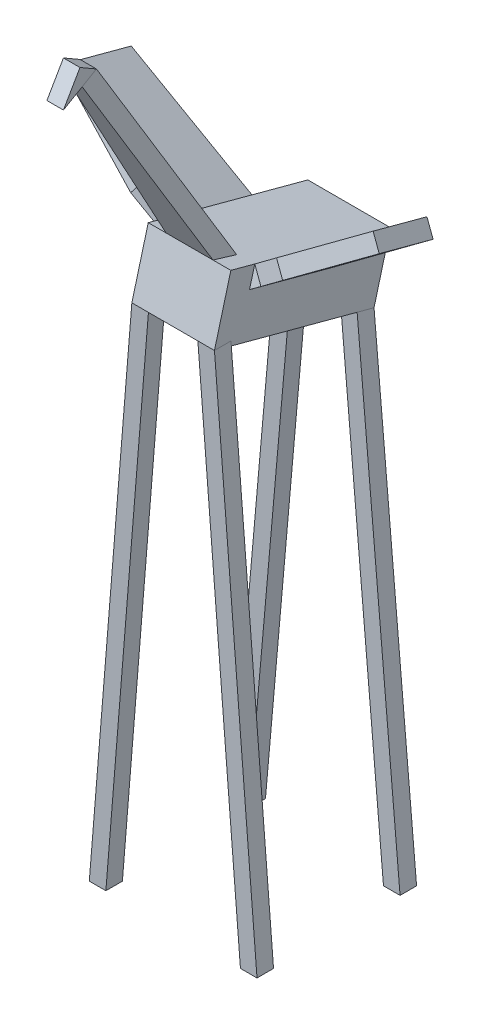
SolidWorks part; units mm, degrees
ref_plane "Front Plane" through (0, 0, 0) normal (0, 0, 1) x (1, 0, 0)
ref_plane "Top Plane" through (0, 0, 0) normal (0, 1, 0) x (1, 0, 0)
ref_plane "Right Plane" through (0, 0, 0) normal (1, 0, 0) x (0, 0, -1)
sketch "Sketch1" plane through (0, 0, 0) normal (0, 0, 1) x (1, 0, 0)
  line L0 (-381, 4776.3484) -> (-773.5586, 0)
  line L1 (-381, 5381.4823) -> (381, 5381.4823)
  line L2 (-381, 5381.4823) -> (-381, 4776.3484)
  line L3 (-381, 4776.3484) -> (381, 4776.3484)
  line L4 (381, 5381.4823) -> (381, 4776.3484)
  line L5 (381, 4776.3484) -> (773.5586, 0)
  line L6 (773.5586, 0) -> (-773.5586, 0) construction
  line L7 (0, 4776.3484) -> (0, 0) construction
  line L8 (381, 5381.4823) -> (1363.861, 6109.7421)
  line L9 (-381, 5381.4823) -> (-1372.9032, 6116.442)
  line L10 (-216.3677, 5381.4823) -> (-76.2, 7210.2823)
  line L11 (-76.2, 7210.2823) -> (76.2, 7210.2823)
  line L12 (76.2, 7210.2823) -> (216.3677, 5381.4823)
  line L13 (0, 5381.4823) -> (0, 7210.2823) construction
  dimension "D1" = 762
  dimension "D2" = 1828.8
  dimension "D3" = 152.4
ref_plane "Plane5" through (0, 360.491, 1345.3706) normal (0, 0.2588, 0.9659) x (1, 0, 0)
sketch "Sketch9" plane through (0, 360.491, 1345.3706) normal (0, 0.2588, 0.9659) x (1, 0, 0)
  line L0 (-381, 5198.1127) -> (381, 5198.1127)
  line L1 (-381, 5198.1127) -> (381, 5198.1127) construction
  line L2 (381, 5198.1127) -> (381, 4613.5982)
  line L3 (381, 4613.5982) -> (-381, 4613.5982)
  line L4 (-381, 4613.5982) -> (-381, 5198.1127)
  line L5 (381, 5198.1127) -> (381, 4613.5982) construction
extrude "Boss-Extrude6" add sketch "Sketch9" against normal blind 1524
ref_plane "Plane2" through (-2331.0967, 3146.0531, -842.9824) normal (-0.582, 0.7855, -0.2105) x (0.8132, 0.5622, -0.1506)
sketch "Sketch3" plane through (-2331.0967, 3146.0531, -842.9824) normal (-0.582, 0.7855, -0.2105) x (0.8132, 0.5622, -0.1506)
  line L0 (3335.1545, -1164.2301) -> (3619.5368, -1240.4301)
  line L2 (3619.5368, -1240.4301) -> (4543.811, -1240.4301)
  line L3 (4543.811, -1240.4301) -> (4543.811, -726.0886)
  line L4 (4543.811, -726.0886) -> (3335.1545, -402.2301)
  line L5 (3335.1545, -402.2301) -> (3182.7545, -402.2301)
  line L6 (3182.7545, -402.2301) -> (3182.7545, -1164.2301)
  line L7 (3182.7545, -1164.2301) -> (3335.1545, -1164.2301)
  line L8 (3335.1545, 131.1699) -> (3335.1545, -1392.8301) construction
  dimension "D1" = 152.4
  dimension "D2" = 762
  dimension "D3" = 76.2
  dimension "D4" = 15
  dimension "D5" = 152.4
extrude "Boss-Extrude7" add sketch "Sketch3" against normal blind 152.4
mirror "Mirror1" about plane through (0, 0, 0) normal (1, 0, 0) of "Boss-Extrude7"
ref_plane "Plane3" through (0, 1345.3706, -2330.2502) normal (0, -0.5, 0.866) x (1, 0, 0)
sketch "Sketch4" plane through (0, 1345.3706, -2330.2502) normal (0, -0.5, 0.866) x (1, 0, 0)
  line L0 (-216.3677, 4660.5004) -> (-76.2, 6794.1004)
  line L1 (-76.2, 6794.1004) -> (76.2, 6794.1004)
  line L2 (76.2, 6794.1004) -> (216.3677, 4660.5004)
  line L3 (216.3677, 4660.5004) -> (226.3797, 4508.1004)
  line L4 (226.3797, 4508.1004) -> (-226.3797, 4508.1004)
  line L5 (-226.3797, 4508.1004) -> (-216.3677, 4660.5004)
  line L6 (-76.2, 6244.2876) -> (76.2, 6244.2876) construction
  line L7 (0, 6794.1004) -> (0, 4660.5004) construction
  dimension "D1" = 152.4
  dimension "D2" = 2133.6
ref_plane "Plane4" through (0, 0, -762) normal (0, 0, 1) x (1, 0, 0)
extrude "Boss-Extrude8" add sketch "Sketch4" against normal blind 152.4
sketch "Sketch13" plane through (0, 0, 0) normal (1, 0, 0) x (0, 0, -1)
  line L0 (-934.8177, 7305.4341) -> (-1239.6177, 7129.4577)
  line L1 (-1239.6177, 7129.4577) -> (-1087.2177, 7393.4223)
  line L2 (-1087.2177, 7393.4223) -> (-934.8177, 7305.4341)
  dimension "D1" = 60
  dimension "D2" = 152.4
extrude "Boss-Extrude11" add sketch "Sketch13" along normal mid plane 152.4
ref_plane "Plane6" through (0, 0, 151.2835) normal (0, 0, 1) x (1, 0, 0)
sketch "Sketch10" plane through (0, 0, 151.2835) normal (0, 0, 1) x (1, 0, 0)
  line L0 (-381, 4816.8846) -> (-773.5586, 0)
  line L1 (-773.5586, 0) -> (773.5586, 0) construction
  line L2 (773.5586, 0) -> (381, 4816.8846)
  line L3 (-381, 4816.8846) -> (-228.0947, 4816.8846)
  line L4 (-228.0947, 4816.8846) -> (-620.6533, 0)
  line L5 (-620.6533, 0) -> (-773.5586, 0)
  line L6 (773.5586, 0) -> (620.6533, 0)
  line L7 (620.6533, 0) -> (228.0947, 4816.8846)
  line L8 (228.0947, 4816.8846) -> (381, 4816.8846)
  line L9 (0, 0) -> (0, 4816.8846) construction
  line L10 (-381, 4816.8846) -> (381, 4816.8846) construction
  dimension "D1" = 152.4
extrude "Boss-Extrude9" add sketch "Sketch10" against normal blind 152.4
ref_plane "Plane7" through (0, 0, -1320.7875) normal (0, 0, 1) x (1, 0, 0)
sketch "Sketch12" plane through (0, 0, -1320.7875) normal (0, 0, 1) x (1, 0, 0)
  line L0 (381, 4422.4444) -> (773.5586, 0)
  line L1 (773.5586, 0) -> (-773.5586, 0) construction
  line L2 (-773.5586, 0) -> (-381, 4422.4444)
  line L3 (-381, 4987.0421) -> (-381, 4422.4444) construction
  line L4 (-381, 4422.4444) -> (381, 4422.4444) construction
  line L5 (0, 4422.4444) -> (0, 0) construction
  line L6 (381, 4422.4444) -> (228.0008, 4422.4444) construction
  line L7 (228.0008, 4422.4444) -> (620.5593, 0)
  line L8 (620.5593, 0) -> (773.5586, 0)
  line L9 (-381, 4422.4444) -> (-228.0008, 4422.4444) construction
  line L10 (-228.0008, 4422.4444) -> (-620.5593, 0)
  line L11 (-620.5593, 0) -> (-773.5586, 0)
  line L12 (381, 4422.4444) -> (367.4722, 4574.8444)
  line L13 (367.4722, 4574.8444) -> (214.473, 4574.8444)
  line L14 (214.473, 4574.8444) -> (228.0008, 4422.4444)
  line L15 (-228.0008, 4422.4444) -> (-214.473, 4574.8444)
  line L16 (-214.473, 4574.8444) -> (-367.4722, 4574.8444)
  line L17 (-367.4722, 4574.8444) -> (-381, 4422.4444)
  dimension "D1" = 152.4
  dimension "D2" = 152.4
extrude "Boss-Extrude10" add sketch "Sketch12" along normal blind 152.4
